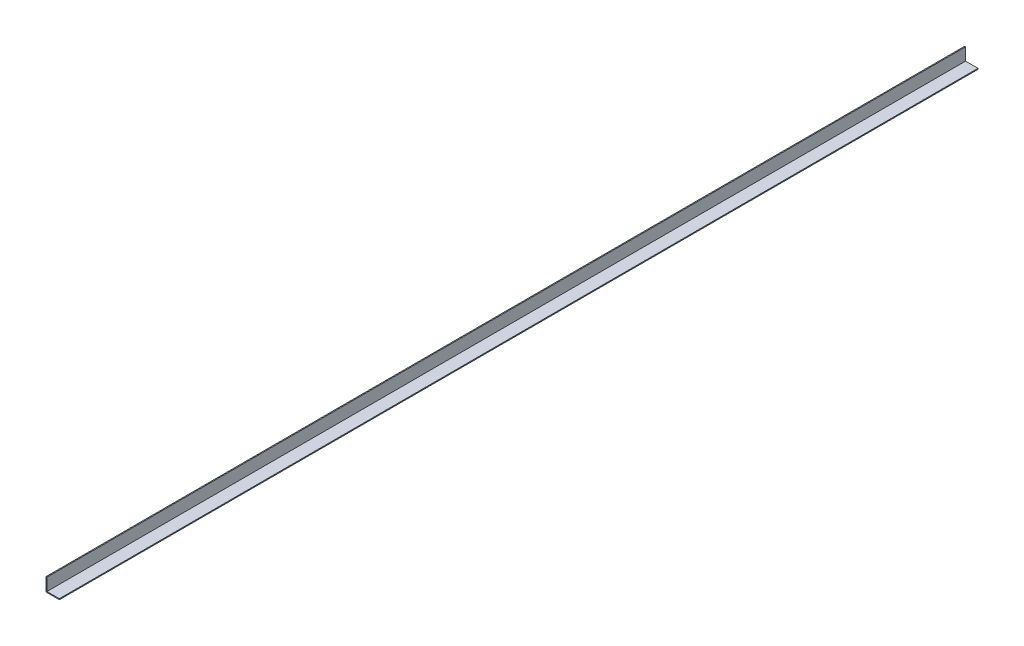
SolidWorks part; units mm, degrees
material "ASTM A36 Acero"
ref_plane "Alzado" through (0, 0, 0) normal (0, 0, 1) x (1, 0, 0)
ref_plane "Planta" through (0, 0, 0) normal (0, 1, 0) x (1, 0, 0)
ref_plane "Vista lateral" through (0, 0, 0) normal (1, 0, 0) x (0, 0, -1)
sketch "Croquis1" plane through (0, 0, 0) normal (0, 0, 1) x (1, 0, 0)
  line L0 (0, 88.9) -> (0, 0)
  line L1 (0, 0) -> (88.9, 0)
  line L2 (88.9, 0) -> (88.9, 6.35)
  line L3 (88.9, 6.35) -> (6.35, 6.35)
  line L4 (6.35, 6.35) -> (6.35, 88.9)
  line L5 (6.35, 88.9) -> (0, 88.9)
  dimension "D1" = 6.35
  dimension "D2" = 88.9
extrude "Saliente-Extruir1" add sketch "Croquis1" against normal blind 6100
